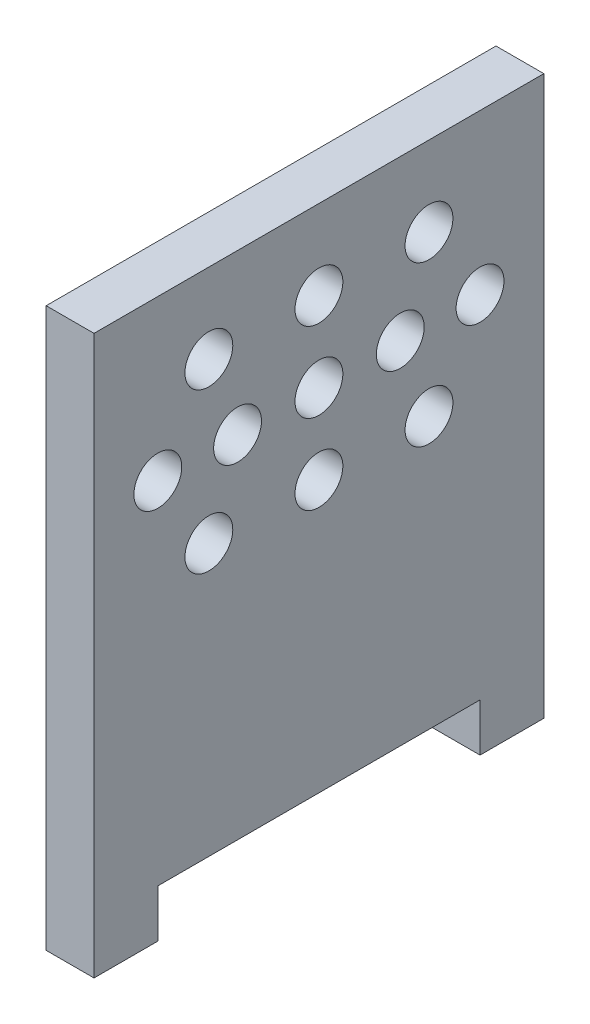
SolidWorks part; units mm, degrees
ref_plane "Plan de face" through (0, 0, 0) normal (0, 0, 1) x (1, 0, 0)
ref_plane "Plan de dessus" through (0, 0, 0) normal (0, 1, 0) x (1, 0, 0)
ref_plane "Plan de droite" through (0, 0, 0) normal (1, 0, 0) x (0, 0, -1)
ref_plane "Plan1" through (-3, 0, 0) normal (-1, 0, 0) x (0, -1, 0)
sketch "Esquisse1" plane through (-3, 0, 0) normal (-1, 0, 0) x (0, -1, 0)
  line L0 (35, 27.2) -> (0, 27.2)
  line L1 (0, 27.2) -> (0, -1)
  line L2 (0, -1) -> (35, -1)
  line L3 (35, -1) -> (35, 3)
  line L4 (35, 3) -> (32, 3)
  line L5 (32, 3) -> (32, 23.2)
  line L6 (32, 23.2) -> (35, 23.2)
  line L7 (35, 23.2) -> (35, 27.2)
  line L8 (15, 20) -> (5, 6.2) construction
  line L9 (12.5628, 40.5726) -> (2.5628, 26.7726) construction
  line L13 (15, 6.2) -> (5, 20) construction
  circle A0 centre (5, 6.2) radius 1.5
  circle A1 centre (10, 8) radius 1.5
  circle A2 centre (15, 20) radius 1.5
  circle A3 centre (5, 20) radius 1.5
  circle A4 centre (15, 6.2) radius 1.5
  circle A5 centre (10, 13.1) radius 1.5
  circle A6 centre (10, 3) radius 1.5
  circle A7 centre (5, 13.1) radius 1.5
  circle A8 centre (15, 13.1) radius 1.5
  circle A9 centre (10, 23.2) radius 1.5
  circle A10 centre (10, 18.2) radius 1.5
  dimension "D1" = 35
  dimension "D2" = 28.2
  dimension "D3" = 35
  dimension "D4" = 20.2
  dimension "D5" = 4
  dimension "D6" = 4
  dimension "D7" = 3
  dimension "D8" = 3
  dimension "D9" = 7.2
  dimension "D10" = 7.2
  dimension "D11" = 7.2
  dimension "D12" = 7.2
  dimension "D13" = 10
  dimension "D14" = 10
  dimension "D15" = 5
  dimension "D16" = 5
  dimension "D17" = 6.9
  dimension "D18" = 6.9
  dimension "D19" = 6.9
  dimension "D20" = 6.9
  dimension "D21" = 4
  dimension "D22" = 4
  dimension "D23" = 5.1
  dimension "D24" = 5.1
extrude "Boss.-Extru.1" add sketch "Esquisse1" against normal blind 3
